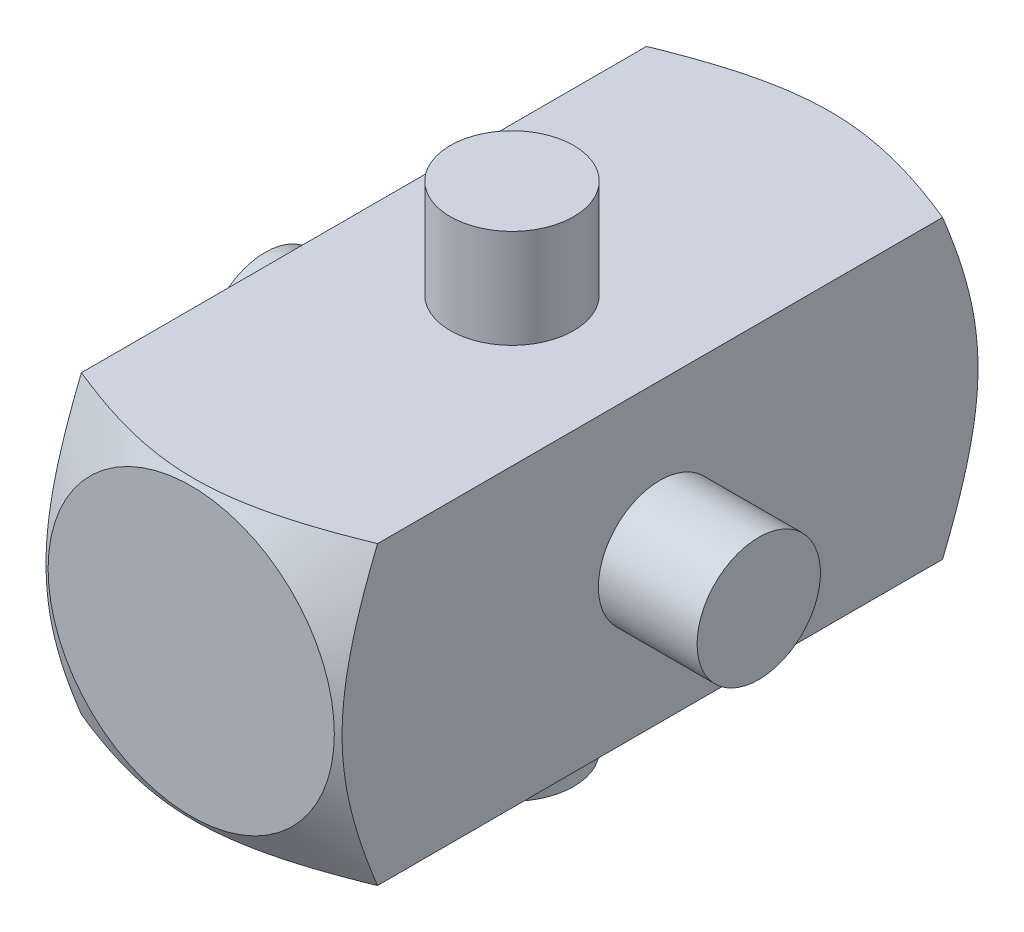
SolidWorks part; units mm, degrees
ref_plane "Front Plane" through (0, 0, 0) normal (0, 0, 1) x (1, 0, 0)
ref_plane "Top Plane" through (0, 0, 0) normal (0, 1, 0) x (1, 0, 0)
ref_plane "Right Plane" through (0, 0, 0) normal (1, 0, 0) x (0, 0, -1)
sketch "Sketch1" plane through (0, 0, 0) normal (0, 0, 1) x (1, 0, 0)
  line L1 (-3.81, -3.81) -> (3.81, -3.81)
  line L2 (-3.81, -3.81) -> (-3.81, 3.81)
  line L3 (-3.81, 3.81) -> (3.81, 3.81)
  line L4 (3.81, -3.81) -> (3.81, 3.81)
  line L5 (-3.81, -3.81) -> (3.81, 3.81) construction
  line L6 (-3.81, 3.81) -> (3.81, -3.81) construction
  point P0 (0, 0)
  dimension "D1" = 7.62
extrude "Boss-Extrude1" add sketch "Sketch1" along normal mid plane 16.51
ref_plane "Plane1" through (0, 0, 0) normal (0, -1, 0) x (-1, 0, 0)
ref_plane "Plane2" through (0, 0, 0) normal (-1, 0, 0) x (0, 0, 1)
sketch "Sketch2" plane through (0, 0, 0) normal (0, -1, 0) x (-1, 0, 0)
  line L0 (0, 8.255) -> (0, -8.255) construction
  line L3 (-3.683, 8.255) -> (-12.573, 8.255)
  line L4 (-12.573, 8.255) -> (-12.573, -8.255)
  line L5 (-12.573, -8.255) -> (-3.683, -8.255)
  line L6 (-3.683, -8.255) -> (-11.303, -3.8556)
  line L7 (-11.303, -3.8556) -> (-11.303, 3.8556)
  line L8 (-11.303, 3.8556) -> (-3.683, 8.255)
  line L10 (3.81, 8.255) -> (-3.81, 8.255) construction
  line L11 (3.81, -8.255) -> (-3.81, -8.255) construction
  line L12 (-3.81, -8.255) -> (-3.81, 8.255) construction
  point P8 (-3.81, 0)
  point P20 (-11.303, 0)
  dimension "D1" = 1.27
  dimension "D2" = 7.62
  dimension "D3" = 0.127
  dimension "D4" = 30
  dimension "D5" = 30
revolve "Cut-Revolve2" cut sketch "Sketch2" angle 360 about L0
sketch "Sketch3" plane through (0, 0, 0) normal (0, -1, 0) x (1, 0, 0)
  line L0 (-3.683, -8.255) -> (3.683, -8.255) construction
  circle A0 centre (0, 0) radius 1.5875
  dimension "D1" = 3.175
  dimension "D2" = 8.255
extrude "Boss-Extrude2" add sketch "Sketch3" along normal mid plane 12.7
sketch "Sketch4" plane through (0, 0, 0) normal (-1, 0, 0) x (0, 0, 1)
  line L0 (8.255, -3.683) -> (8.255, 3.683) construction
  circle A0 centre (0, 0) radius 1.5875
  dimension "D1" = 3.175
  dimension "D2" = 8.255
extrude "Boss-Extrude3" add sketch "Sketch4" along normal mid plane 12.7
